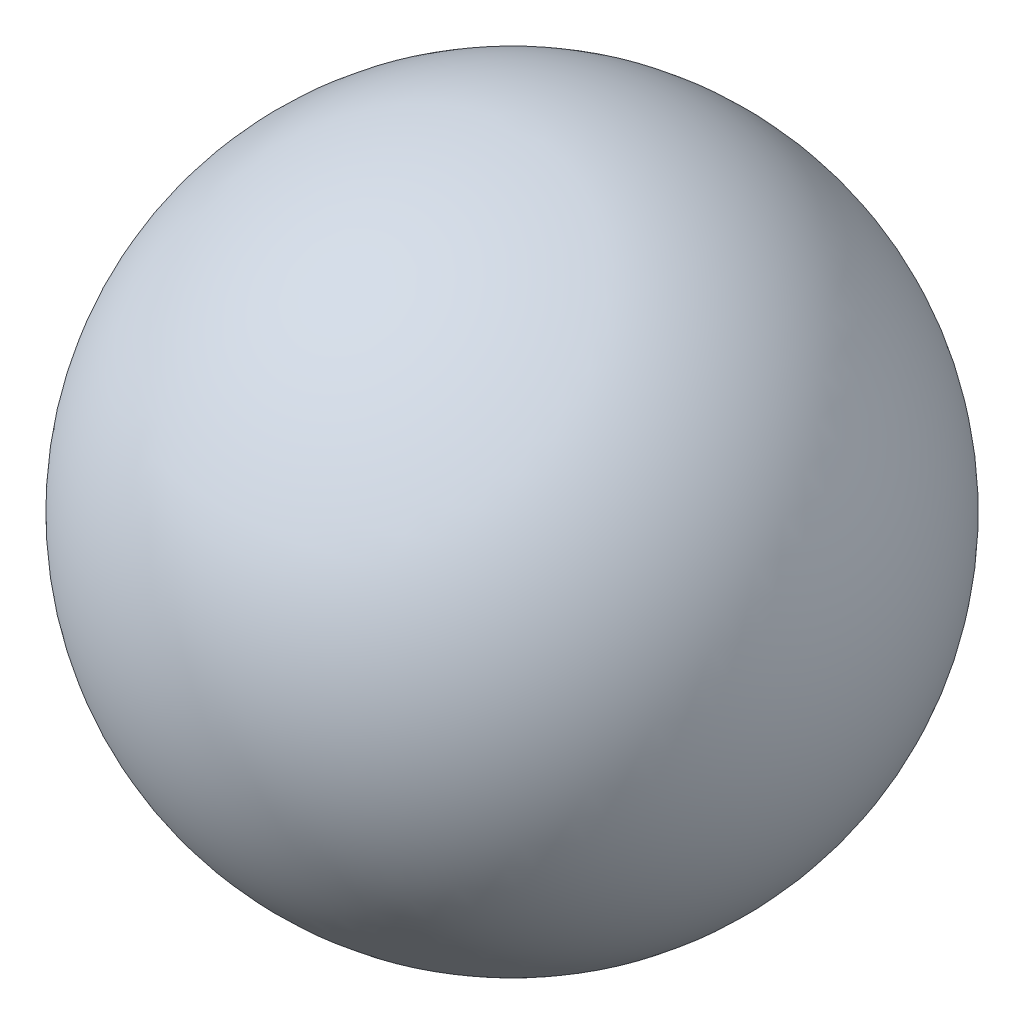
SolidWorks part; units mm, degrees
ref_plane "Front Plane" through (0, 0, 0) normal (1, 0, 0) x (0, 1, 0)
ref_plane "Top Plane" through (0, 0, 0) normal (0, 0, 1) x (0, 1, 0)
ref_plane "Right Plane" through (0, 0, 0) normal (0, 1, 0) x (-1, 0, 0)
sketch "Sketch1" plane through (0, 0, 0) normal (1, 0, 0) x (0, 1, 0)
  line L0 (-30, 0) -> (30, 0)
  arc A0 (30, 0) -> (-30, 0) centre (0, 0) ccw
  dimension "D1" = 60
revolve "Revolve1" add sketch "Sketch1" angle 360 about L0
